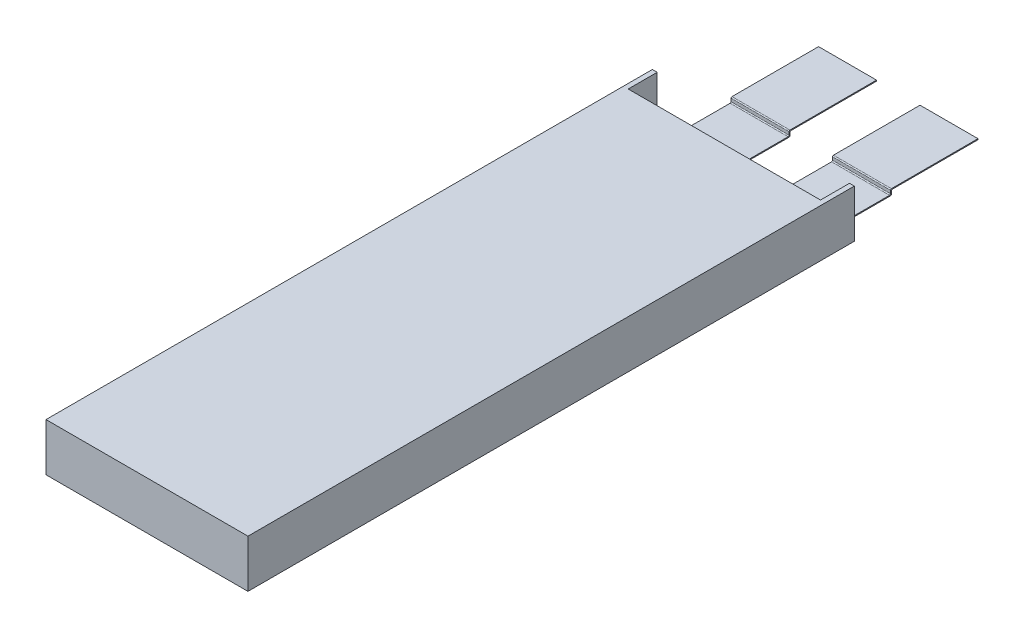
SolidWorks part; units mm, degrees
ref_plane "Front Plane" through (0, 0, 0) normal (0, 0, 1) x (1, 0, 0)
ref_plane "Top Plane" through (0, 0, 0) normal (0, 1, 0) x (1, 0, 0)
ref_plane "Right Plane" through (0, 0, 0) normal (1, 0, 0) x (0, 0, -1)
sketch "Sketch1" plane through (0, 0, 0) normal (0, 1, 0) x (1, 0, 0)
  line L1 (20.9, 62.75) -> (-20.9, 62.75)
  line L2 (20.9, 62.75) -> (20.9, -62.75)
  line L3 (20.9, -62.75) -> (-20.9, -62.75)
  line L4 (-20.9, 62.75) -> (-20.9, -62.75)
  line L5 (20.9, 62.75) -> (-20.9, -62.75) construction
  line L6 (20.9, -62.75) -> (-20.9, 62.75) construction
  point P0 (0, 0)
  dimension "D1" = 41.8
  dimension "D2" = 125.5
extrude "Boss-Extrude1" add sketch "Sketch1" along normal blind 1
sketch "Sketch2" plane through (0, 1, 0) normal (0, 1, 0) x (1, 0, 0)
  line L0 (-20.9, 62.75) -> (-20.9, -62.75) construction
  line L1 (20.9, 56.75) -> (-20.9, 56.75)
  line L2 (20.9, 56.75) -> (20.9, -62.75)
  line L3 (20.9, -62.75) -> (-20.9, -62.75)
  line L4 (-20.9, 56.75) -> (-20.9, -62.75)
  line L5 (20.9, 56.75) -> (-20.9, -62.75) construction
  line L6 (20.9, -62.75) -> (-20.9, 56.75) construction
  line L7 (20.9, 62.75) -> (-20.9, 62.75) construction
  line L8 (-20.9, -62.75) -> (20.9, -62.75) construction
  line L10 (20.9, -62.75) -> (20.9, 62.75) construction
  point P0 (0, -3)
  point P11 (15.8573, 56.75)
  dimension "D1" = 6
extrude "Boss-Extrude2" add sketch "Sketch2" along normal blind 8.9
sketch "Sketch3" plane through (0, 1, 0) normal (0, 1, 0) x (1, 0, 0)
  line L0 (20.9, 56.75) -> (-20.9, 56.75) construction
  line L1 (-20.9, 62.75) -> (-19.9, 62.75)
  line L2 (-20.9, 62.75) -> (-20.9, 56.75)
  line L3 (-20.9, 56.75) -> (-19.9, 56.75)
  line L4 (-19.9, 62.75) -> (-19.9, 56.75)
  line L5 (0, 56.75) -> (0, 62.75) construction
  line L6 (20.9, 56.75) -> (-20.9, 56.75) construction
  line L7 (20.9, 62.75) -> (-20.9, 62.75) construction
  dimension "D1" = 1
extrude "Boss-Extrude3" add sketch "Sketch3" along normal blind 8.9
sketch "Sketch4" plane through (0, 0, 0) normal (1, 0, 0) x (0, 0, -1)
  line L0 (74.8376, 1.2) -> (92.75, 1.2)
  line L2 (92.75, 1.2) -> (92.75, 1)
  line L3 (92.75, 1) -> (75.0376, 1)
  line L4 (62.75, 0) -> (74.6376, 0)
  line L5 (62.75, 0) -> (62.75, 0.2)
  line L6 (62.75, 1) -> (62.75, 0) construction
  line L7 (62.75, 0.2) -> (74.4376, 0.2)
  line L8 (74.6376, 1) -> (74.6376, 0.4)
  line L9 (74.8376, 0.8) -> (74.8376, 0.2)
  arc A0 (74.8376, 1.2) -> (74.6376, 1) centre (74.8376, 1) ccw
  arc A1 (74.4376, 0.2) -> (74.6376, 0.4) centre (74.4376, 0.4) ccw
  arc A2 (74.6376, 0) -> (74.8376, 0.2) centre (74.6376, 0.2) ccw
  arc A3 (75.0376, 1) -> (74.8376, 0.8) centre (75.0376, 0.8) ccw
  point P8 (74.8376, 0)
  point P14 (0, 0)
  point P15 (74.9933, 1.2)
  point P16 (0, 0)
  point P17 (74.6649, 1.2)
  dimension "D6" = 0.2
  dimension "D1" = 0.2
  dimension "D2" = 0.2
  dimension "D3" = 1
  dimension "D4" = 30
  dimension "D5" = 0.2
extrude "Boss-Extrude4" add sketch "Sketch4" along normal blind 12 from offset 4.5
mirror "Mirror1" about plane through (0, 0, 0) normal (1, 0, 0) of "Boss-Extrude4", "Boss-Extrude3"
